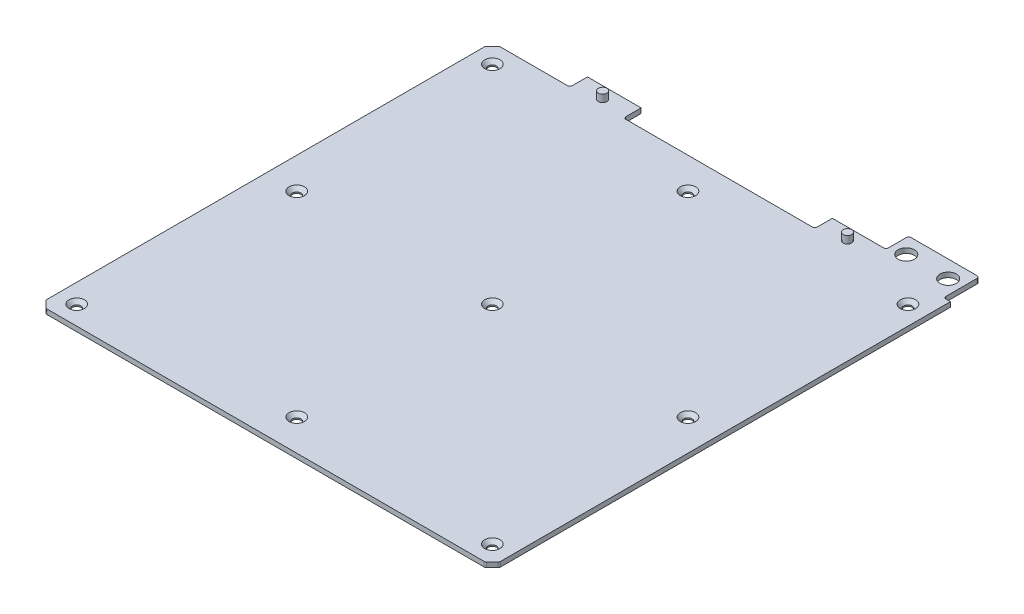
SolidWorks part; units mm, degrees
ref_plane "Front Plane" through (0, 0, 0) normal (0, 0, 1) x (1, 0, 0)
ref_plane "Top Plane" through (0, 0, 0) normal (0, 1, 0) x (1, 0, 0)
ref_plane "Right Plane" through (0, 0, 0) normal (1, 0, 0) x (0, 0, -1)
sketch "Esquisse4" plane through (0, 0, 0) normal (0, 1, 0) x (1, 0, 0)
  line L0 (93, -90) -> (93, 93)
  line L1 (93, 93) -> (-90, 93)
  line L2 (-90, 93) -> (-93, 90)
  line L3 (-93, 90) -> (-93, -90)
  line L4 (-93, -90) -> (-90, -93)
  line L5 (-90, -93) -> (90, -93)
  line L6 (90, -93) -> (93, -90)
extrude "Boss.-Extru.1" add sketch "Esquisse4" against normal blind 2 separate body
sketch "Esquisse5" plane through (0, 0, -93) normal (0, 0, -1) x (-1, 0, 0)
  line L0 (-93, 0) -> (61.2, 0)
  line L1 (61.2, 0) -> (61.2, -2)
  line L2 (61.2, -2) -> (-93, -2)
  line L3 (-93, -2) -> (-93, 0)
extrude "Boss.-Extru.2" add sketch "Esquisse5" along normal blind 16.5
ref_plane "Plan2" through (0, -2, 0) normal (0, -1, 0) x (-1, 0, 0)
sketch "Esquisse9" plane through (0, -2, 0) normal (0, -1, 0) x (-1, 0, 0)
  line L0 (-93, 94.8) -> (-90.2, 94.8)
  line L1 (-90.2, 94.8) -> (-90.2, 109.5)
  line L2 (-90.2, 109.5) -> (-93, 109.5)
  line L3 (-93, 109.5) -> (-93, 94.8)
extrude "Enlèv. mat.-Extru.1" cut sketch "Esquisse9" against normal through all
sketch "Esquisse10" plane through (0, -2, 0) normal (0, -1, 0) x (1, 0, 0)
  line L0 (61.2, -109.5) -> (61.2, -100.2)
  line L1 (61.2, -100.2) -> (-61.2, -100.2)
  line L2 (-61.2, -100.2) -> (-61.2, -109.5)
  line L3 (-61.2, -109.5) -> (61.2, -109.5)
extrude "Enlèv. mat.-Extru.2" cut sketch "Esquisse10" against normal through all
sketch "Esquisse11" plane through (0, -2, 0) normal (0, -1, 0) x (1, 0, 0)
  line L0 (-39.2, -100.2) -> (39.2, -100.2)
  line L1 (39.2, -100.2) -> (39.2, -93)
  line L2 (39.2, -93) -> (-39.2, -93)
  line L3 (-39.2, -93) -> (-39.2, -100.2)
extrude "Enlèv. mat.-Extru.3" cut sketch "Esquisse11" against normal through all
hole_wizard "CSK for M3 Flat Head Machine Screw1" positions "Esquisse13" profile "Esquisse12" countersink size "M3" standard "ANSI Metric"
sketch "Esquisse13" plane through (0, 0, 0) normal (0, 1, 0) x (1, 0, 0)
  point P0 (0, 80.2)
  point P1 (0, -80.2)
  point P2 (85.2, 85.2)
  point P3 (80.2, 0)
  point P4 (85.2, -85.2)
  point P5 (-85.2, -85.2)
  point P6 (-85.2, 85.2)
  point P7 (-80.2, 0)
  point P8 (0, 0)
sketch "Esquisse12" plane through (0, 0, -80.2) normal (1, 0, 0) x (0, 0, 1)
  line L0 (0, 0) -> (0, 2)
  line L1 (0, 2) -> (1.7, 2)
  line L2 (1.7, 2) -> (1.7, 1.45)
  line L3 (1.7, 1.45) -> (3.15, 0)
  line L5 (3.15, 0) -> (0, 0)
  line L6 (-1.7, 1.45) -> (-3.15, 0) construction
  line L10 (0, 2) -> (-1.7, 2) construction
  line L11 (0, -6.35) -> (0, 107.95) construction
  dimension "Hole Dia." = 3.4
  dimension "Hole Depth" = 2
  dimension "Near C'Sink Dia." = 6.3
  dimension "Near C'Sink Angle" = 90
  dimension "Drill Angle" = 180
hole_wizard "Ø6.7 (6.7) Diameter Hole1" positions "Esquisse15" profile "Esquisse14" hole size "Ø6.7" standard "ANSI Metric"
sketch "Esquisse15" plane through (0, -2, 0) normal (0, -1, 0) x (-1, 0, 0)
  point P0 (-84.4, 102.5)
  point P1 (-67.2, 102.5)
sketch "Esquisse14" plane through (84.4, -2, -102.5) normal (1, 0, 0) x (0, 0, -1)
  line L0 (0, 0) -> (0, 2)
  line L1 (0, 2) -> (3.35, 2)
  line L2 (3.35, 2) -> (3.35, 0)
  line L5 (3.35, 0) -> (0, 0)
  line L10 (0, 2) -> (-3.35, 2) construction
  line L11 (0, -6.35) -> (0, 107.95) construction
  dimension "Hole Dia." = 6.7
  dimension "Hole Depth" = 2
  dimension "Drill Angle" = 180
fillet "Congé1" radius 1 13 edges at (-93, -1, -90) (93, -1, 90) (90.2, -1, -94.8) (-61.2, -1, -93) (-90, -1, 93) (-39.2, -1, -93) (90, -1, 93) (39.2, -1, -93) (-93, -1, 90) (61.2, -1, -100.2) (-90, -1, -93) (61.2, -1, -109.5) (90.2, -1, -109.5)
ref_plane "Plan3" through (0, 0, -95.4) normal (0, 0, 1) x (1, 0, 0)
sketch "Esquisse20" plane through (0, 0, -95.4) normal (0, 0, 1) x (1, 0, 0)
  line L0 (-48.45, 3) -> (-50.2, 3)
  line L1 (-50.2, 3) -> (-50.2, 0)
  line L2 (-50.2, 0) -> (-48.45, 0)
  line L3 (-48.45, 0) -> (-48.45, 3)
  line L4 (-50.2, 3) -> (-50.2, 0) construction
revolve "Révolution2" add sketch "Esquisse20" angle 360 about L1
sketch "Esquisse26" plane through (0, 0, -95.4) normal (0, 0, 1) x (1, 0, 0)
  line L0 (51.95, 3) -> (50.2, 3)
  line L1 (50.2, 3) -> (50.2, 0)
  line L2 (50.2, 0) -> (51.95, 0)
  line L3 (51.95, 0) -> (51.95, 3)
  line L4 (50.2, 3) -> (50.2, 0) construction
revolve "Révolution3" add sketch "Esquisse26" angle 360 about L1
